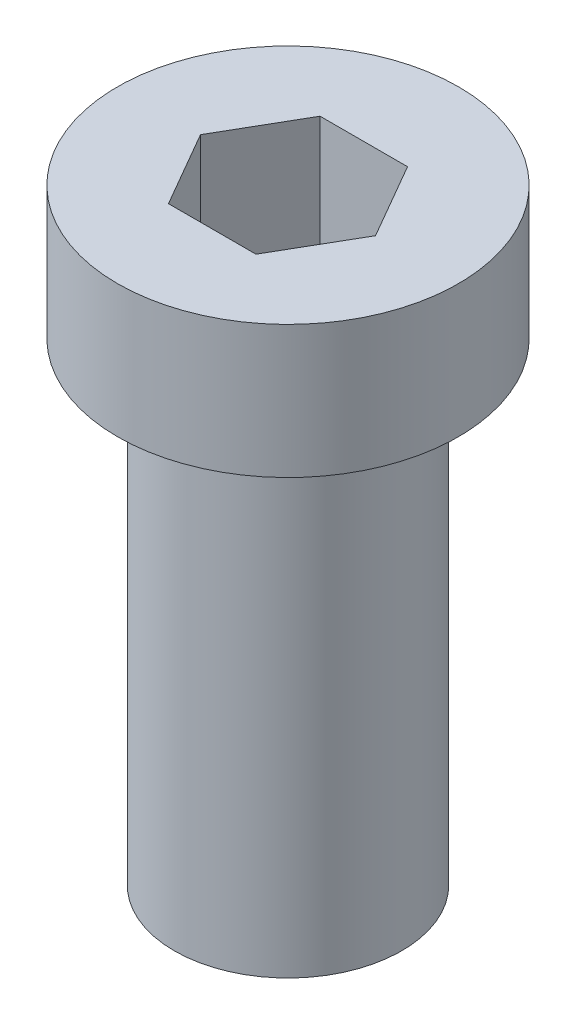
SolidWorks part; units mm, degrees
material "AISI 304"
ref_plane "Front Plane" through (0, 0, 0) normal (0, 0, 1) x (1, 0, 0)
ref_plane "Top Plane" through (0, 0, 0) normal (0, 1, 0) x (1, 0, 0)
ref_plane "Right Plane" through (0, 0, 0) normal (1, 0, 0) x (0, 0, -1)
sketch "Sketch1" plane through (0, 0, 0) normal (0, 0, 1) x (1, 0, 0)
  line L0 (0, 61.6916) -> (0, -59.3578) construction
  line L1 (0, -25) -> (6, -25)
  line L2 (6, -25) -> (6, 0)
  line L3 (6, 0) -> (9, 0)
  line L4 (9, 0) -> (9, 7)
  line L5 (9, 7) -> (0, 7)
  line L6 (0, 7) -> (0, -25)
  dimension "D1" = 25
  dimension "D2" = 18
  dimension "D3" = 12
  dimension "D4" = 7
revolve "Revolve1" add sketch "Sketch1" angle 360 about L0
sketch "Sketch2" plane through (0, 7, 0) normal (0, 1, 0) x (-1, 0, 0)
  line L1 (-2.3094, -4) -> (2.3094, -4)
  line L2 (2.3094, -4) -> (4.6188, 0)
  line L3 (4.6188, 0) -> (2.3094, 4)
  line L4 (2.3094, 4) -> (-2.3094, 4)
  line L5 (-2.3094, 4) -> (-4.6188, 0)
  line L6 (-4.6188, 0) -> (-2.3094, -4)
  circle A0 centre (0, 0) radius 4 construction
  dimension "D1" = 8
extrude "Cut-Extrude1" cut sketch "Sketch2" against normal blind 6
